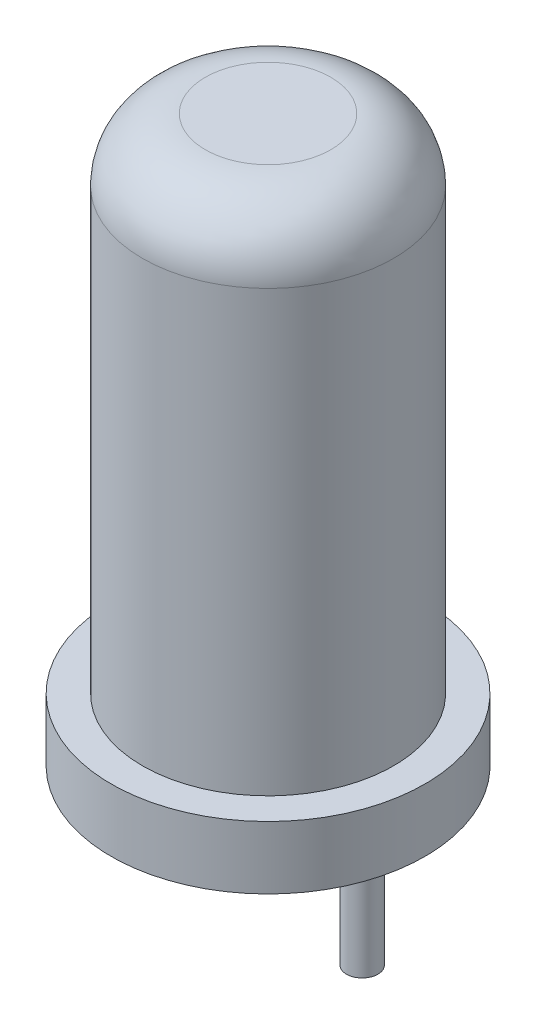
SolidWorks part; units mm, degrees
ref_plane "Front Plane" through (0, 0, 0) normal (0, 0, 1) x (1, 0, 0)
ref_plane "Top Plane" through (0, 0, 0) normal (0, 1, 0) x (1, 0, 0)
ref_plane "Right Plane" through (0, 0, 0) normal (1, 0, 0) x (0, 0, -1)
sketch "Sketch1" plane through (0, 0, 0) normal (0, 0, 1) x (1, 0, 0)
  line L0 (0, 0) -> (0, 9)
  line L1 (-2, 6) -> (-2, 1)
  line L2 (-2.5, 1) -> (-2.5, 0)
  line L3 (-2.5, 0) -> (0, 0)
  line L4 (-2.5, 1) -> (-2, 1)
  line L5 (0, 9) -> (-1, 9)
  line L6 (-2, 8) -> (-2, 6)
  arc A1 (-1, 9) -> (-2, 8) centre (-1, 8) ccw
  dimension "D3" = 1
  dimension "D1" = 9
  dimension "D2" = 1
  dimension "D4" = 2
  dimension "D5" = 5
  dimension "D6" = 0.5
  dimension "D7" = 1
  dimension "D8" = 2.5
revolve "Revolve1" add sketch "Sketch1" angle 360 about L0
sketch "Sketch2" plane through (0, 0, 0) normal (0, -1, 0) x (1, 0, 0)
  circle A0 centre (1.5, 0) radius 0.25
  circle A1 centre (-1.5, 0) radius 0.25
  dimension "D1" = 0.5
  dimension "D2" = 0.5
  dimension "D3" = 3
  dimension "D4" = 1.5
extrude "Boss-Extrude1" add sketch "Sketch2" along normal blind 2
